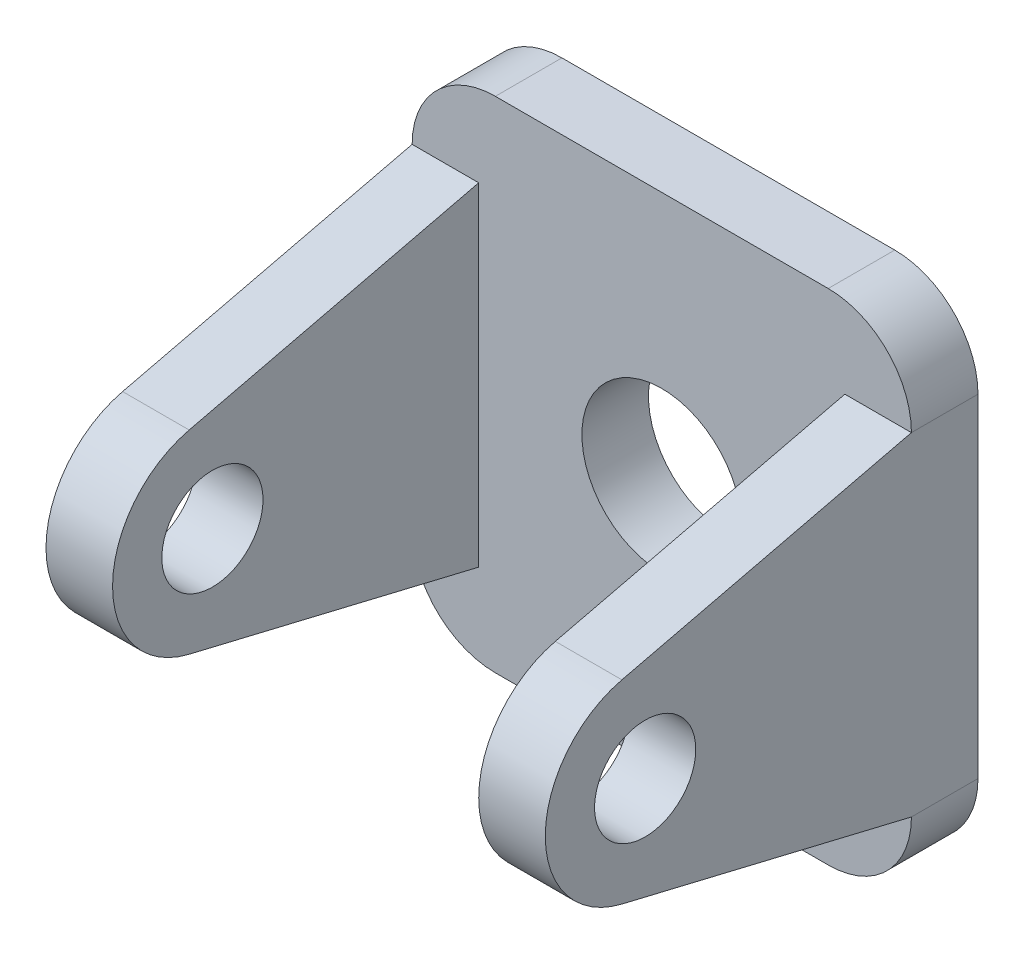
SolidWorks part; units mm, degrees
ref_plane "Front Plane" through (0, 0, 0) normal (1, 0, 0) x (0, 1, 0)
ref_plane "Top Plane" through (0, 0, 0) normal (0, 0, 1) x (0, 1, 0)
ref_plane "Right Plane" through (0, 0, 0) normal (0, 1, 0) x (-1, 0, 0)
sketch "Sketch1" plane through (0, 0, 0) normal (0, 0, 1) x (0, 1, 0)
  line L1 (-25, -37.5) -> (25, -37.5)
  line L2 (-37.5, -25) -> (-37.5, 25)
  line L3 (-25, 37.5) -> (25, 37.5)
  line L4 (37.5, -25) -> (37.5, 25)
  line L5 (-37.5, -37.5) -> (37.5, 37.5) construction
  line L6 (-37.5, 37.5) -> (37.5, -37.5) construction
  arc A0 (-25, -37.5) -> (-37.5, -25) centre (-25, -25) cw
  arc A1 (25, -37.5) -> (37.5, -25) centre (25, -25) ccw
  arc A2 (25, 37.5) -> (37.5, 25) centre (25, 25) cw
  arc A3 (-37.5, 25) -> (-25, 37.5) centre (-25, 25) cw
  point P0 (0, 0)
  dimension "D2" = 12.5
  dimension "D1" = 75
extrude "Boss-Extrude1" add sketch "Sketch1" along normal blind 10
sketch "Sketch2" plane through (37.5, 0, 0) normal (1, 0, 0) x (0, 1, 0)
  line L0 (0, 50) -> (0, 0) construction
  line L1 (-25, 10) -> (25, 10) construction
  line L2 (-25, 10) -> (-14.5878, 53.4924)
  line L3 (25, 10) -> (14.5878, 53.4924)
  line L4 (25, 10) -> (25, 0) construction
  line L5 (37.5, 10) -> (25, 10) construction
  circle A0 centre (0, 50) radius 15
  circle A1 centre (0, 50) radius 7.6
  dimension "D2" = 30
  dimension "D3" = 15.2
  dimension "D1" = 40
extrude "Boss-Extrude2" add sketch "Sketch2" against normal blind 10
mirror "Mirror1" about plane through (0, 0, 0) normal (1, 0, 0) of "Boss-Extrude2"
sketch "Sketch3" plane through (0, 0, 10) normal (0, 0, 1) x (1, 0, 0)
  line L0 (0, 37.5) -> (0, -37.5) construction
  line L1 (25, 37.5) -> (-25, 37.5) construction
  line L2 (-25, -37.5) -> (25, -37.5) construction
  circle A0 centre (0, 32.5) radius 1.6
  circle A1 centre (0, -32.5) radius 1.6
  dimension "D1" = 3.2
  dimension "D2" = 5
  dimension "D3" = 5
extrude "Cut-Extrude1" [suppressed] cut sketch "Sketch3" against normal through all
sketch "Sketch4" plane through (0, 0, 10) normal (0, 0, 1) x (1, 0, 0)
  circle A0 centre (0, 0) radius 12
  dimension "D1" = 24
extrude "Cut-Extrude2" cut sketch "Sketch4" against normal through all
